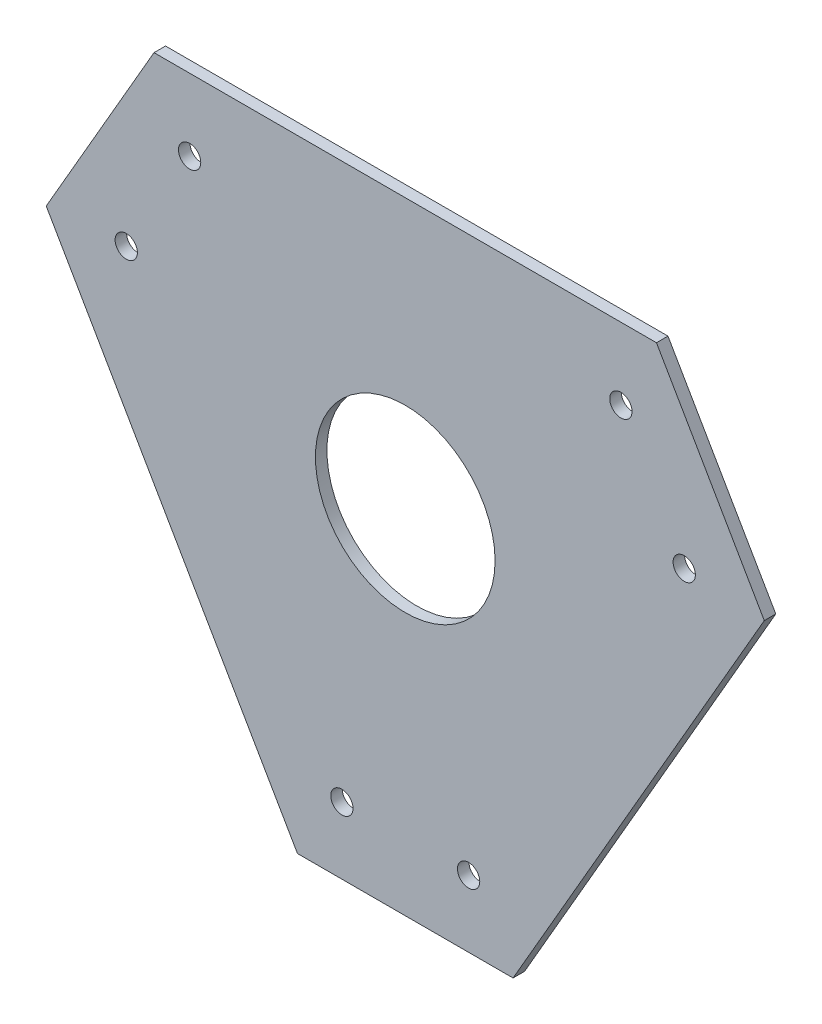
SolidWorks part; units mm, degrees
ref_plane "Front Plane" through (0, 0, 0) normal (0, 0, 1) x (1, 0, 0)
ref_plane "Top Plane" through (0, 0, 0) normal (0, 1, 0) x (1, 0, 0)
ref_plane "Right Plane" through (0, 0, 0) normal (1, 0, 0) x (0, 0, -1)
sketch "Sketch1" plane through (0, 0, 0) normal (0, 0, 1) x (1, 0, 0)
  line L0 (-64.9519, 37.5) -> (0, -75) construction
  line L1 (-38.8157, 12.2308) -> (-8.8157, -39.7308) construction
  line L2 (8.8157, -39.7308) -> (38.8157, 12.2308) construction
  line L3 (-30, 27.5) -> (30, 27.5) construction
  line L4 (0, 0) -> (32.476, -18.75) construction
  line L5 (0, 0) -> (0, 37.5) construction
  line L6 (0, 0) -> (-32.476, -18.75) construction
  line L7 (0, -75) -> (64.9519, 37.5) construction
  line L8 (64.9519, 37.5) -> (-64.9519, 37.5) construction
  line L9 (-34.9519, 37.5) -> (34.9519, 37.5)
  line L10 (49.9519, 11.5192) -> (15, -49.0192)
  line L11 (-15, -49.0192) -> (-49.9519, 11.5192)
  line L12 (-49.9519, 11.5192) -> (-34.9519, 37.5)
  line L13 (34.9519, 37.5) -> (49.9519, 11.5192)
  line L14 (15, -49.0192) -> (-15, -49.0192)
  circle A0 centre (0, 0) radius 37.5 construction
  circle A1 centre (-30, 27.5) radius 1.55
  circle A2 centre (30, 27.5) radius 1.55
  circle A3 centre (38.8157, 12.2308) radius 1.55
  circle A4 centre (8.8157, -39.7308) radius 1.55
  circle A5 centre (-8.8157, -39.7308) radius 1.55
  circle A6 centre (-38.8157, 12.2308) radius 1.55
  circle A7 centre (0, 0) radius 12.5
  point P2 (0, 37.5)
  point P4 (30, 27.5)
  point P5 (38.8157, 12.2308)
  point P6 (8.8157, -39.7308)
  point P7 (-32.476, -18.75)
  point P8 (-8.8157, -39.7308)
  point P9 (-30, 27.5)
  point P12 (-38.8157, 12.2308)
  point P19 (23.8157, -13.75)
  point P20 (0, 27.5)
  point P25 (-23.8157, -13.75)
  point P33 (0, 0)
  point P34 (0, 0)
  point P35 (64.9519, 37.5)
  point P37 (0, -75)
  point P38 (-64.9519, 37.5)
  point P39 (0, 0)
  dimension "D1" = 75
  dimension "D6" = 3.1
  dimension "D7" = 25
  dimension "D2" = 60
  dimension "D3" = 10
  dimension "D4" = 10
  dimension "D5" = 10
  dimension "D8" = 30
  dimension "D9" = 30
  dimension "D11" = 30
  dimension "D12" = 30
extrude "Boss-Extrude1" add sketch "Sketch1" along normal blind 1.6 contours L14 L10 L13 L9 L12 L11 A7 A6 A5 A4 A3 A2 A1
